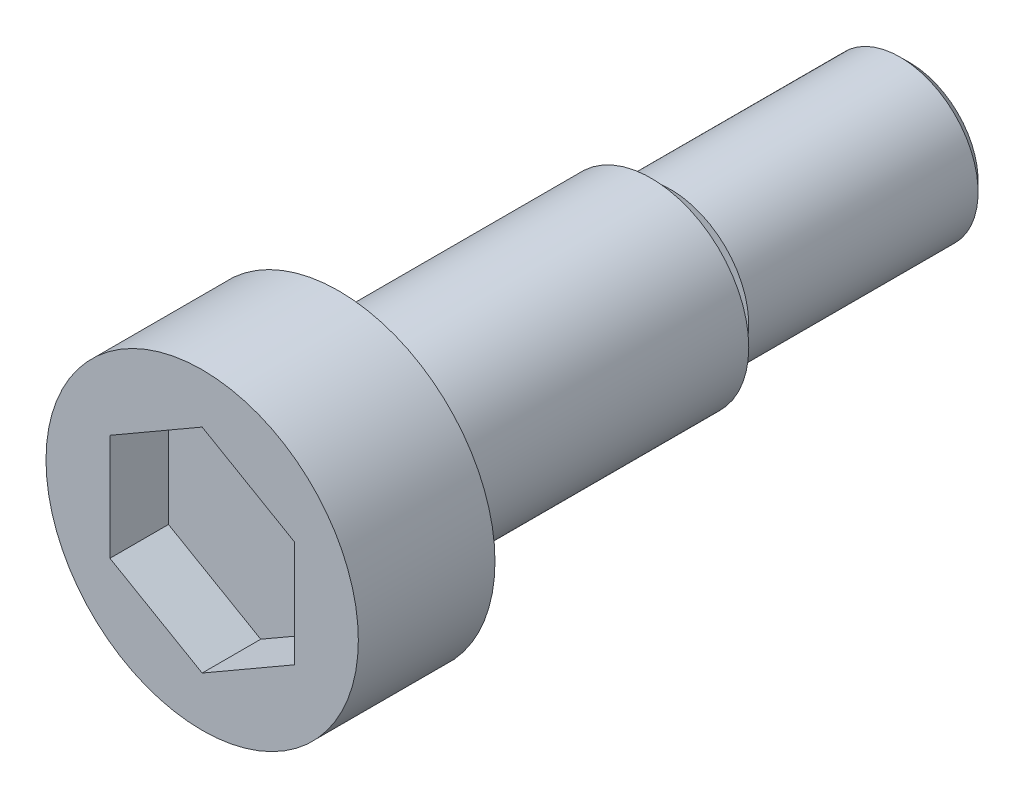
SolidWorks part; units mm, degrees
ref_plane "前视基准面" through (0, 0, 0) normal (0, 0, 1) x (1, 0, 0)
ref_plane "上视基准面" through (0, 0, 0) normal (0, 1, 0) x (1, 0, 0)
ref_plane "右视基准面" through (0, 0, 0) normal (1, 0, 0) x (0, 0, -1)
sketch "草图2" plane through (0, 0, 0) normal (0, 0, 1) x (1, 0, 0)
  circle A0 centre (0, 0) radius 5
extrude "凸台-拉伸1" add sketch "草图2" along normal blind 16
sketch "草图3" plane through (0, 0, 16) normal (0, 0, 1) x (1, 0, 0)
  circle A0 centre (0, 0) radius 8
extrude "凸台-拉伸2" add sketch "草图3" along normal blind 7
sketch "草图4" plane through (0, 0, 0) normal (0, 0, -1) x (-1, 0, 0)
  circle A0 centre (0, 0) radius 4
extrude "凸台-拉伸3" add sketch "草图4" along normal blind 13.25
cosmetic thread "装饰螺纹线2" parameters "D2"=6.619
sketch "草图5" plane through (0, 0, 23) normal (0, 0, 1) x (1, 0, 0)
  line L1 (0, 5.4562) -> (-4.7252, 2.7281)
  line L2 (-4.7252, 2.7281) -> (-4.7252, -2.7281)
  line L3 (-4.7252, -2.7281) -> (0, -5.4562)
  line L4 (0, -5.4562) -> (4.7252, -2.7281)
  line L5 (4.7252, -2.7281) -> (4.7252, 2.7281)
  line L6 (4.7252, 2.7281) -> (0, 5.4562)
  circle A0 centre (0, 0) radius 4.7252 construction
extrude "切除-拉伸1" cut sketch "草图5" against normal blind 3
chamfer "倒角1" distance 0.5 angle 45 1 edges at (-4, 0, -13.25)
sketch "草图6" plane through (0, 0, 0) normal (0, 0, -1) x (-1, 0, 0)
  circle A0 centre (0, 0) radius 4
  circle A1 centre (0, 0) radius 3.5
extrude "切除-拉伸2" cut sketch "草图6" along normal blind 1
